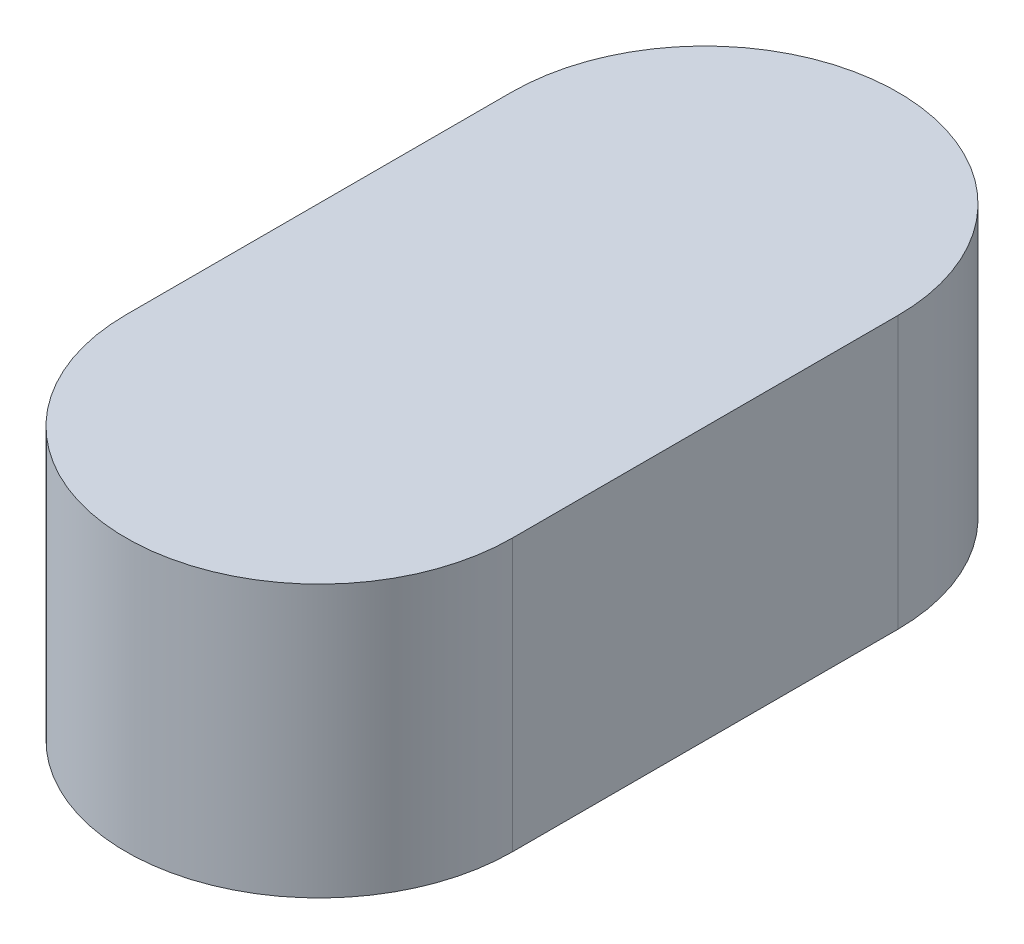
SolidWorks part; units mm, degrees
ref_plane "Front Plane" through (0, 0, 0) normal (0, 0, 1) x (1, 0, 0)
ref_plane "Top Plane" through (0, 0, 0) normal (0, 1, 0) x (1, 0, 0)
ref_plane "Right Plane" through (0, 0, 0) normal (1, 0, 0) x (0, 0, -1)
sketch "Sketch1" plane through (0, 0, 0) normal (0, 1, 0) x (1, 0, 0)
  line L1 (0, 0) -> (762, 0)
  line L2 (0, 0) -> (0, 1524)
  line L3 (0, 1524) -> (762, 1524)
  line L4 (762, 0) -> (762, 1524)
  dimension "D1" = 762
  dimension "D2" = 1524
sketch "Sketch2" plane through (0, 0, 0) normal (0, 1, 0) x (1, 0, 0)
  line L0 (523.3695, -852.4411) -> (523.3695, -1224.8907) construction
  line L1 (710.1273, -852.4411) -> (710.1273, -1224.8907)
  line L2 (336.6118, -852.4411) -> (336.6118, -1224.8907)
  arc A0 (710.1273, -852.4411) -> (336.6118, -852.4411) centre (523.3695, -852.4411) ccw
  arc A1 (336.6118, -1224.8907) -> (710.1273, -1224.8907) centre (523.3695, -1224.8907) ccw
  point P2 (523.3695, -1038.6659)
extrude "Boss-Extrude1" add sketch "Sketch2" along normal blind 262.636
